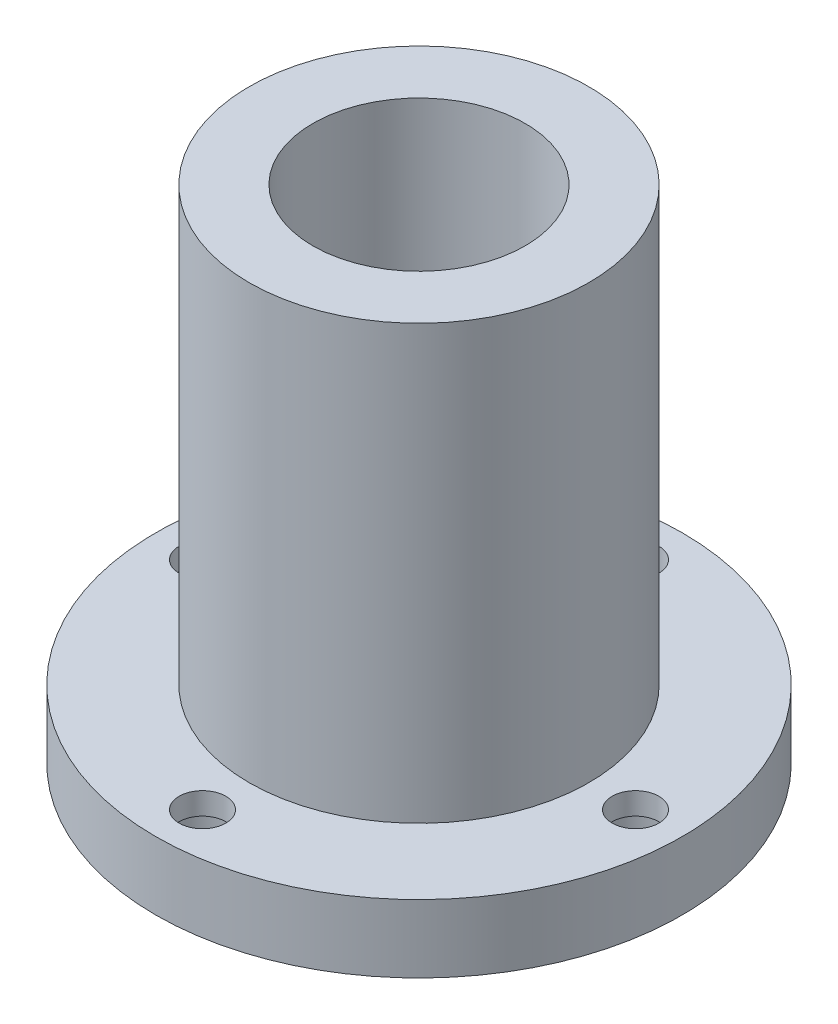
SolidWorks part; units mm, degrees
ref_plane "Front Plane" through (0, 0, 0) normal (0, 0, 1) x (1, 0, 0)
ref_plane "Top Plane" through (0, 0, 0) normal (0, 1, 0) x (1, 0, 0)
ref_plane "Right Plane" through (0, 0, 0) normal (1, 0, 0) x (0, 0, -1)
sketch "Sketch1" plane through (0, 0, 0) normal (0, 1, 0) x (1, 0, 0)
  circle A0 centre (0, 0) radius 31
  dimension "D1" = 62
extrude "Boss-Extrude1" add sketch "Sketch1" along normal blind 8
sketch "Sketch2" plane through (0, 8, 0) normal (0, 1, 0) x (1, 0, 0)
  circle A0 centre (0, 0) radius 20
  dimension "D1" = 40
extrude "Boss-Extrude2" add sketch "Sketch2" along normal blind 51
sketch "Sketch3" plane through (0, 59, 0) normal (0, 1, 0) x (1, 0, 0)
  circle A0 centre (0, 0) radius 12.5
  dimension "D1" = 25
extrude "Cut-Extrude1" cut sketch "Sketch3" against normal through all
sketch "Sketch4" plane through (0, 0, 0) normal (0, -1, 0) x (1, 0, 0)
  line L0 (0, -25.5) -> (0, 25.5) construction
  line L1 (-25.5, 0) -> (25.5, 0) construction
  circle A0 centre (0, 0) radius 25.5 construction
  circle A1 centre (0, -25.5) radius 4.6
  circle A2 centre (-25.5, 0) radius 4.6
  circle A3 centre (0, 25.5) radius 4.6
  circle A4 centre (25.5, 0) radius 4.6
  dimension "D1" = 51
  dimension "D2" = 9.2
extrude "Cut-Extrude2" cut sketch "Sketch4" against normal blind 5.4
sketch "Sketch5" plane through (0, 5.4, 0) normal (0, -1, 0) x (1, 0, 0)
  circle A0 centre (25.5, 0) radius 2.75
  circle A1 centre (0, -25.5) radius 2.75
  circle A2 centre (-25.5, 0) radius 2.75
  circle A3 centre (0, 25.5) radius 2.75
  dimension "D1" = 5.5
extrude "Cut-Extrude3" cut sketch "Sketch5" against normal through all
